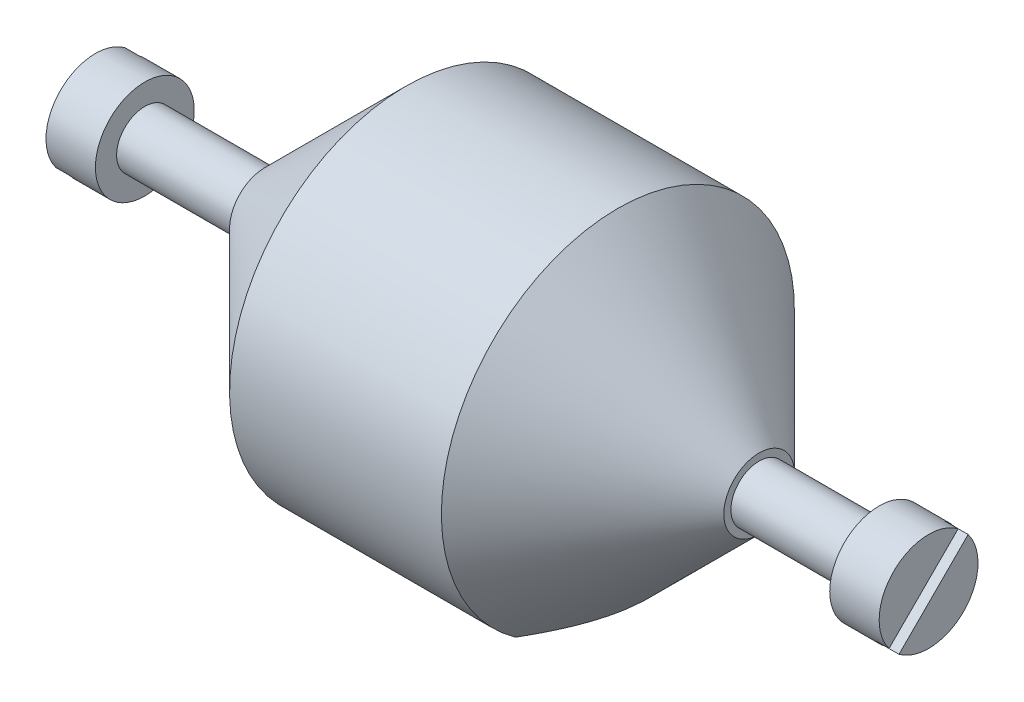
SolidWorks part; units mm, degrees
ref_plane "Front Plane" through (0, 0, 0) normal (0, 0, 1) x (1, 0, 0)
ref_plane "Top Plane" through (0, 0, 0) normal (0, 1, 0) x (1, 0, 0)
ref_plane "Right Plane" through (0, 0, 0) normal (1, 0, 0) x (0, 0, -1)
sketch "Sketch1" plane through (0, 0, 0) normal (1, 0, 0) x (0, 0, -1)
  circle A0 centre (0, 0) radius 12.5
  dimension "D1" = 25
extrude "Boss-Extrude1" add sketch "Sketch1" along normal mid plane 35
sketch "Sketch2" plane through (0, 0, 0) normal (1, 0, 0) x (0, 0, -1)
  circle A0 centre (0, 0) radius 2
  dimension "D1" = 4
extrude "Boss-Extrude2" add sketch "Sketch2" along normal mid plane 52
chamfer "Chamfer1" distance 10 angle 45 2 edges at (-17.5, 0, -12.5) (17.5, 0, -12.5)
sketch "Sketch3" plane through (0, 0, 0) normal (1, 0, 0) x (0, 0, -1)
  line L1 (-13.8538, -10.172) -> (15.1435, -10.172)
  line L2 (-13.8538, -10.172) -> (-13.8538, -17.3693)
  line L3 (-13.8538, -17.3693) -> (15.1435, -17.3693)
  line L4 (15.1435, -10.172) -> (15.1435, -17.3693)
extrude "Cut-Extrude1" cut sketch "Sketch3" against normal mid plane 40
sketch "Sketch4" plane through (0, -10.172, 0) normal (0, -1, 0) x (1, 0, 0)
  circle A0 centre (0, 0) radius 5
extrude "Cut-Extrude2" cut sketch "Sketch4" against normal blind 5
sketch "Sketch5" plane through (-26, 0, 0) normal (-1, 0, 0) x (0, 0, 1)
  circle A0 centre (0, 0) radius 3.5
  dimension "D1" = 7
extrude "Boss-Extrude3" add sketch "Sketch5" along normal blind 3.5
sketch "Sketch6" plane through (-29.5, 0, 0) normal (-1, 0, 0) x (0, 0, 1)
  line L0 (-3.9341, 4.6412) -> (5.6307, -4.9235)
  line L1 (-4.6412, 3.9341) -> (4.9235, -5.6307)
  line L2 (-4.6412, 3.9341) -> (-3.9341, 4.6412)
  line L3 (4.9235, -5.6307) -> (5.8052, -4.749)
  circle M3 centre (0, 0) radius 3.5
  dimension "D2" = 0.5
  dimension "D1" = 1
extrude "Cut-Extrude6" cut sketch "Sketch6" against normal blind 1 contours L1 L0 M3
mirror "Mirror1" about plane through (0, 0, 0) normal (1, 0, 0) of "Cut-Extrude6", "Boss-Extrude3"
sketch "Sketch9" plane through (0, -5.172, 0) normal (0, -1, 0) x (1, 0, 0)
  circle A0 centre (0, 0) radius 5
sketch "Sketch11" plane through (0, -10.172, 0) normal (0, -1, 0) x (1, 0, 0)
  circle A0 centre (0, 0) radius 5
  circle A1 centre (0, 0) radius 1.25
  dimension "D1" = 2.5
extrude "Boss-Extrude4" add sketch "Sketch11" against normal up to surface (5 mm away) up to face at (0, -5.172, -5)
sketch "Sketch12" plane through (0, -10.172, 0) normal (0, -1, 0) x (1, 0, 0)
  circle A0 centre (0, 0) radius 2.5
  dimension "D1" = 5
extrude "Cut-Extrude7" cut sketch "Sketch12" against normal up to surface (5 mm away) up to face at (0, -5.172, -1.25)
